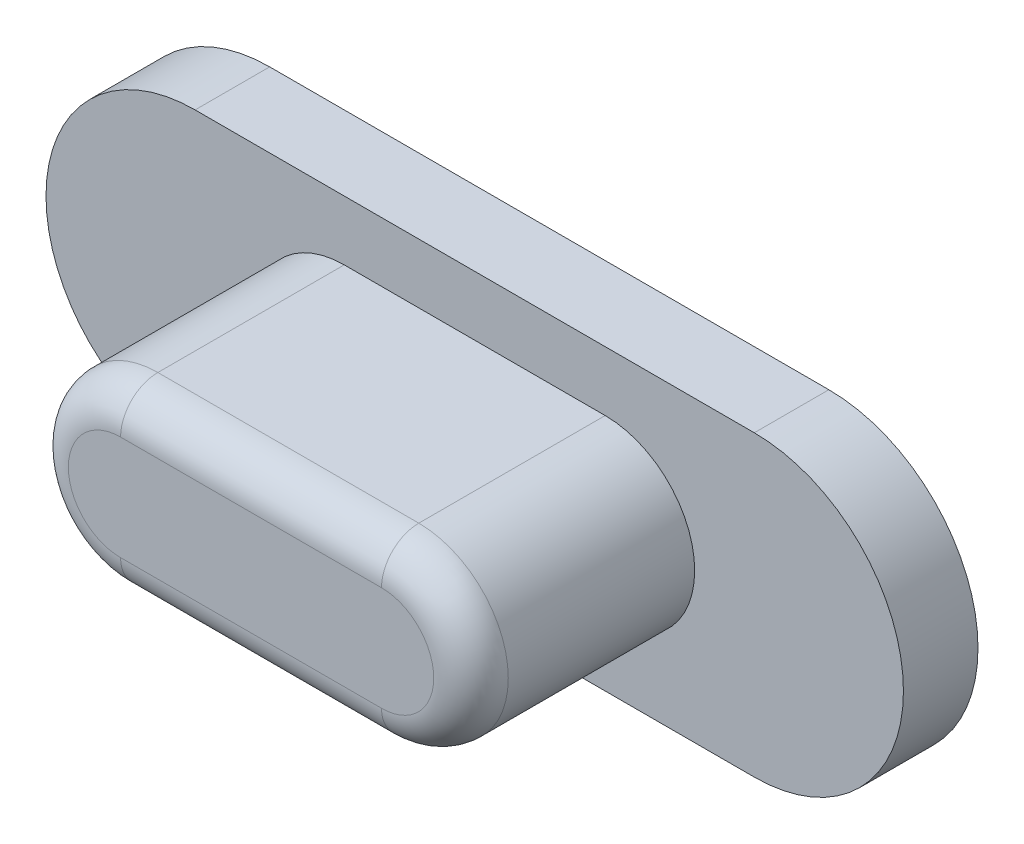
SolidWorks part; units mm, degrees
ref_plane "前视基准面" through (0, 0, 0) normal (0, 0, 1) x (1, 0, 0)
ref_plane "上视基准面" through (0, 0, 0) normal (0, 1, 0) x (1, 0, 0)
ref_plane "右视基准面" through (0, 0, 0) normal (1, 0, 0) x (0, 0, -1)
sketch "草图1" plane through (0, 0, 0) normal (0, 0, 1) x (1, 0, 0)
  line L0 (1.25, 2.5) -> (4.75, 2.5) construction
  line L1 (0, 0) -> (6, 0) construction
  line L2 (0, 0) -> (0, 2.5) construction
  line L3 (0, 2.5) -> (6, 2.5) construction
  line L4 (6, 0) -> (6, 2.5) construction
  line L5 (4.75, 0) -> (1.25, 0) construction
  line L6 (1.25, 2.45) -> (4.75, 2.45)
  line L7 (4.75, 0.05) -> (1.25, 0.05)
  arc A0 (1.25, 2.5) -> (1.25, 0) centre (1.25, 1.25) ccw construction
  arc A1 (4.75, 0) -> (4.75, 2.5) centre (4.75, 1.25) ccw construction
  arc A2 (4.75, 0.05) -> (4.75, 2.45) centre (4.75, 1.25) ccw
  arc A3 (1.25, 2.45) -> (1.25, 0.05) centre (1.25, 1.25) ccw
  dimension "D1" = 6
  dimension "D2" = 2.5
  dimension "D3" = 0.05
extrude "凸台-拉伸1" add sketch "草图1" along normal blind 3
sketch "草图2" plane through (0, 0, 0) normal (0, 0, -1) x (-1, 0, 0)
  line L2 (-4.75, 0.05) -> (-1.25, 0.05)
  line L3 (-4.75, 0.05) -> (-1.25, 0.05)
  line L6 (0.75, 1.25) -> (-6.75, 1.25) construction
  line L7 (0.75, -0.75) -> (-6.75, -0.75)
  line L8 (-1.25, 2.45) -> (-4.75, 2.45)
  line L9 (-1.25, 2.45) -> (-4.75, 2.45)
  line L10 (0.75, 3.25) -> (-6.75, 3.25)
  arc A2 (-1.25, 0.05) -> (-1.25, 2.45) centre (-1.25, 1.25) ccw
  arc A3 (-1.25, 0.05) -> (-1.25, 2.45) centre (-1.25, 1.25) ccw
  arc A6 (0.75, -0.75) -> (0.75, 3.25) centre (0.75, 1.25) ccw
  arc A7 (-6.75, 3.25) -> (-6.75, -0.75) centre (-6.75, 1.25) ccw
  arc A8 (-4.75, 2.45) -> (-4.75, 0.05) centre (-4.75, 1.25) ccw
  arc A9 (-4.75, 2.45) -> (-4.75, 0.05) centre (-4.75, 1.25) ccw
  point P4 (-3, 1.25)
  dimension "D2" = 4
  dimension "D3" = 2
  dimension "D4" = 2
  dimension "D1" = 0
extrude "凸台-拉伸2" add sketch "草图2" along normal blind 1
fillet "圆角1" radius 0.5 4 edges at (0.05, 1.25, 3) (3, 0.05, 3) (5.95, 1.25, 3) (3, 2.45, 3)
